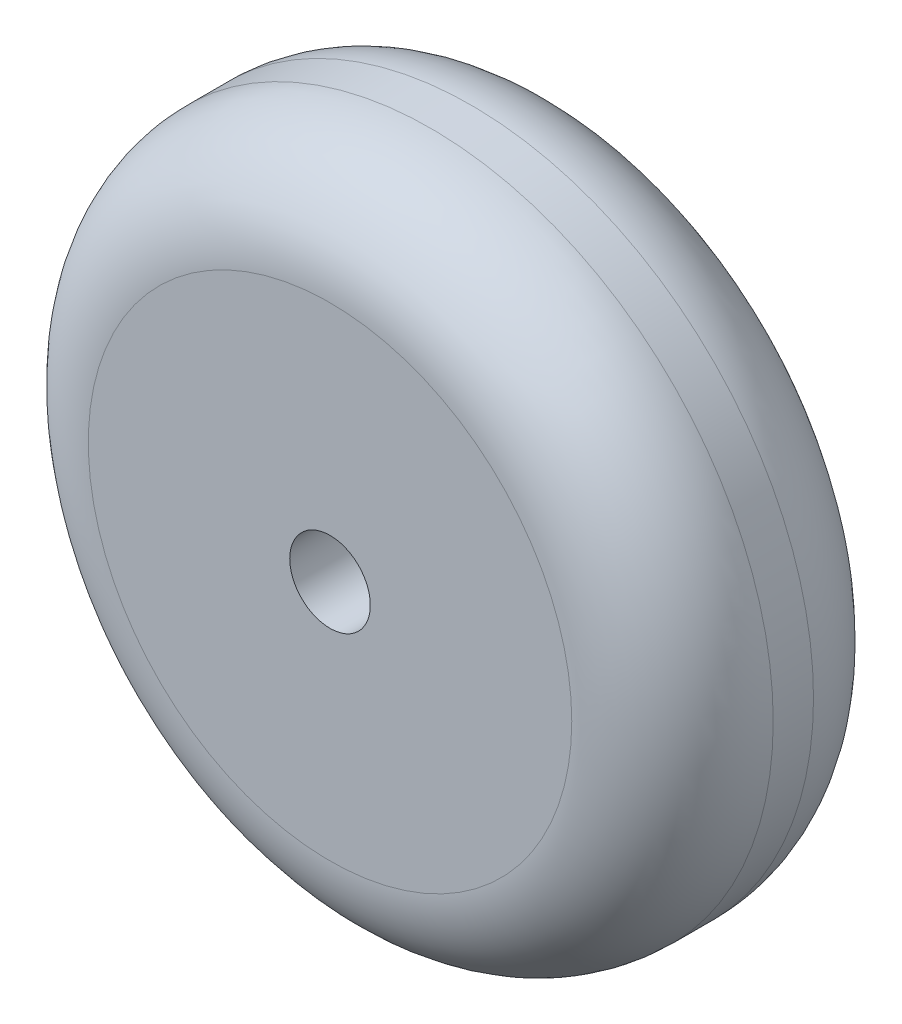
SolidWorks part; units mm, degrees
ref_plane "Front Plane" through (0, 0, 0) normal (0, 0, 1) x (1, 0, 0)
ref_plane "Top Plane" through (0, 0, 0) normal (0, 1, 0) x (1, 0, 0)
ref_plane "Right Plane" through (0, 0, 0) normal (1, 0, 0) x (0, 0, -1)
sketch "Sketch1" plane through (0, 0, 0) normal (0, 0, 1) x (1, 0, 0)
  circle A0 centre (0, 0) radius 85
  dimension "D1" = 170
extrude "WHEEL" add sketch "Sketch1" along normal blind 60
fillet "Fillet1" radius 25 2 edges at (85, 0, 0) (85, 0, 60)
sketch "Sketch4" plane through (0, 0, 0) normal (0, 0, -1) x (-1, 0, 0)
  circle A0 centre (0, 0) radius 10
  dimension "D1" = 20
extrude "Cut-Extrude1" cut sketch "Sketch4" against normal through all
